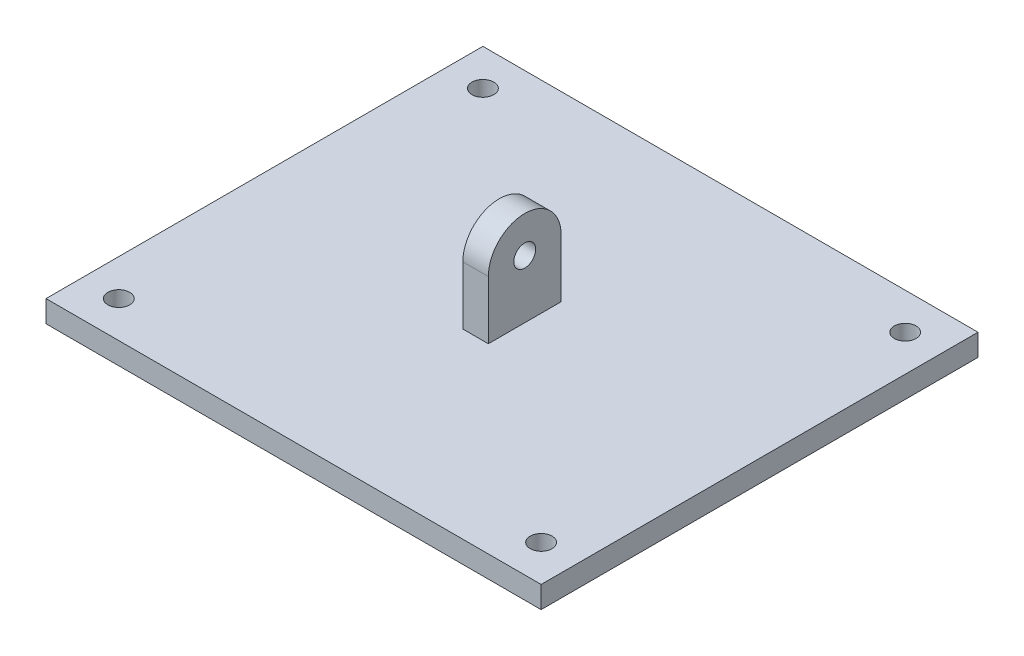
SolidWorks part; units mm, degrees
ref_plane "Alzado" through (0, 0, 0) normal (0, 0, 1) x (1, 0, 0)
ref_plane "Planta" through (0, 0, 0) normal (0, 1, 0) x (1, 0, 0)
ref_plane "Vista lateral" through (0, 0, 0) normal (1, 0, 0) x (0, 0, -1)
sketch "Croquis1" plane through (0, 0, 0) normal (0, 1, 0) x (1, 0, 0)
  line L1 (-34, 30) -> (34, 30)
  line L2 (-34, 30) -> (-34, -30)
  line L3 (-34, -30) -> (34, -30)
  line L4 (34, 30) -> (34, -30)
  line L5 (-34, 30) -> (34, -30) construction
  line L6 (-34, -30) -> (34, 30) construction
  circle A0 centre (-29, 25) radius 1.5
  circle A1 centre (29, 25) radius 1.5
  circle A2 centre (-29, -25) radius 1.5
  circle A3 centre (29, -25) radius 1.5
  point P9 (0, 0)
  dimension "D1" = 29
  dimension "D3" = 3
  dimension "D4" = 3
  dimension "D5" = 50
  dimension "D2" = 58
  dimension "D6" = 50
  dimension "D7" = 25
  dimension "D8" = 60
  dimension "D9" = 68
extrude "Saliente-Extruir2" add sketch "Croquis1" along normal blind 3
sketch "Croquis2" plane through (0, 3, 0) normal (0, 1, 0) x (1, 0, 0)
  line L1 (-2.5, 5) -> (2.5, 5)
  line L2 (-2.5, 5) -> (-2.5, -5)
  line L3 (-2.5, -5) -> (2.5, -5)
  line L4 (2.5, 5) -> (2.5, -5)
  line L5 (-2.5, 5) -> (2.5, -5) construction
  line L6 (-2.5, -5) -> (2.5, 5) construction
  point P0 (0, 0)
extrude "Saliente-Extruir3" add sketch "Croquis2" along normal blind 13
sketch "Croquis3" plane through (2.5, 0, 0) normal (1, 0, 0) x (0, 0, -1)
  line L0 (-5, 16) -> (5, 16) construction
  line L1 (-5, 11) -> (-5, 16)
  line L2 (-5, 16) -> (5, 16)
  line L3 (5, 16) -> (5, 11)
  circle A0 centre (0, 11) radius 5
  line M2 (5, 3) -> (5, 16)
  line M3 (5, 16) -> (-5, 16)
  line M4 (-5, 16) -> (-5, 3)
  dimension "D1" = 5
extrude "Cortar-Extruir1" cut sketch "Croquis3" against normal blind 13 contours A0 L2 M4 | A0 M2 M3
sketch "Croquis4" plane through (2.5, 0, 0) normal (1, 0, 0) x (0, 0, -1)
  circle A0 centre (0, 11) radius 1.5
extrude "Cortar-Extruir2" cut sketch "Croquis4" against normal blind 13
sketch "Croquis6" plane through (0, 0, -5) normal (0, 0, -1) x (-1, 0, 0)
  line L1 (-2.5, 3) -> (-1.75, 3)
  line L2 (-2.5, 3) -> (-2.5, 22.11)
  line L3 (-2.5, 22.11) -> (-1.75, 22.11)
  line L4 (-1.75, 3) -> (-1.75, 22.11)
  line L5 (2.5, 3) -> (1.75, 3)
  line L6 (2.5, 3) -> (2.5, 21.27)
  line L7 (2.5, 21.27) -> (1.75, 21.27)
  line L8 (1.75, 3) -> (1.75, 21.27)
extrude "Cortar-Extruir3" cut sketch "Croquis6" against normal blind 10
